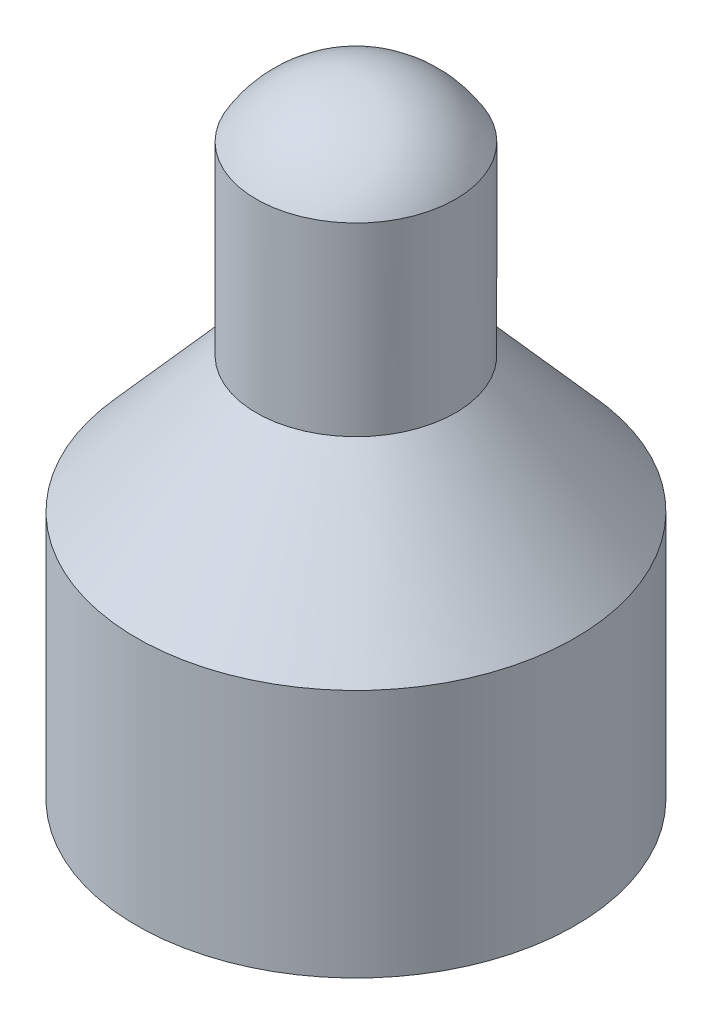
SolidWorks part; units mm, degrees
ref_plane "Plan de face" through (0, 0, 0) normal (0, 0, 1) x (1, 0, 0)
ref_plane "Plan de dessus" through (0, 0, 0) normal (0, 1, 0) x (1, 0, 0)
ref_plane "Plan de droite" through (0, 0, 0) normal (1, 0, 0) x (0, 0, -1)
sketch "Esquisse1" plane through (0, 0, 0) normal (0, 0, 1) x (1, 0, 0)
  line L0 (0, 0) -> (0, 48) construction
  line L1 (12.5, 0) -> (15.4, 0)
  line L2 (15.4, 0) -> (15.4, 17.5)
  line L3 (15.4, 17.5) -> (7, 27)
  line L4 (7, 27) -> (7, 40)
  line L5 (12.5, 0) -> (12.5, 17.15)
  line L6 (12.5, 17.15) -> (11.5, 17.15)
  line L7 (11.5, 17.15) -> (5.4432, 24)
  line L8 (5.4432, 24) -> (0, 24)
  line L9 (0, 44) -> (0, 24)
  arc A0 (7, 40) -> (0, 44) centre (0, 35.875) ccw
  dimension "D4" = 14
  dimension "D1" = 30.8
  dimension "D2" = 25
  dimension "D3" = 40
  dimension "D5" = 17.5
  dimension "D6" = 27
  dimension "D7" = 17.15
  dimension "D8" = 24
  dimension "D9" = 1
  dimension "D10" = 4
revolve "Révolution1" add sketch "Esquisse1" angle 360 about L0
sketch "Esquisse2" plane through (0, 0, 0) normal (0, 0, 1) x (1, 0, 0)
  circle A0 centre (0, 9) radius 1.65
  dimension "D1" = 3.3
  dimension "D2" = 9
extrude "Enlèv. mat.-Extru.1" cut sketch "Esquisse2" against normal through all
ref_plane "Plan1" through (0, 0, -15.3) normal (0, 0, 1) x (1, 0, 0)
sketch "Esquisse3" plane through (0, 0, -15.3) normal (0, 0, 1) x (1, 0, 0)
  circle A0 centre (0, 9) radius 3.35
  circle A1 centre (0, 9) radius 3.35 construction
extrude "Enlèv. mat.-Extru.2" cut sketch "Esquisse3" against normal through all
